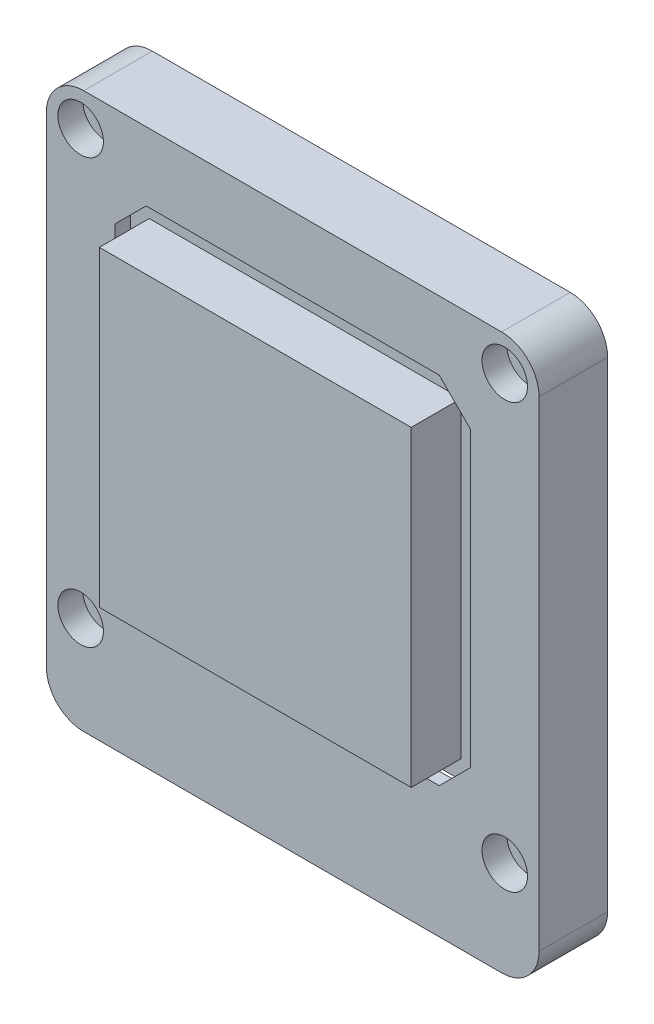
SolidWorks part; units mm, degrees
ref_plane "Front Plane" through (0, 0, 0) normal (1, 0, 0) x (0, 1, 0)
ref_plane "Top Plane" through (0, 0, 0) normal (0, 0, 1) x (0, 1, 0)
ref_plane "Right Plane" through (0, 0, 0) normal (0, 1, 0) x (-1, 0, 0)
sketch "Sketch1" plane through (0, 0, 0) normal (0, 0, 1) x (0, 1, 0)
  line L0 (0, 28) -> (28, 0) construction
  line L1 (0, 0) -> (28, 0)
  line L2 (0, 0) -> (0, 28)
  line L3 (0, 28) -> (28, 28)
  line L4 (28, 0) -> (28, 28)
  line L5 (28, 28) -> (0, 0) construction
  line L7 (1, 28) -> (1, 27) construction
extrude "Boss-Extrude1" add sketch "Sketch1" along normal blind 8.5
sketch "Sketch4" plane through (0, 0, 0) normal (0, 0, -1) x (1, 0, 0)
  line L17 (-28.5, 0.5) -> (-30.5, 0.5) construction
  line L18 (-28.5, 0.5) -> (-28.5, 2.5) construction
  line L19 (-28.5, 2.5) -> (-30.5, 2.5) construction
  line L20 (-30.5, 0.5) -> (-30.5, 2.5) construction
  line L21 (0.5, -28.5) -> (2.5, -28.5) construction
  line L22 (0.5, -28.5) -> (0.5, -30.5) construction
  line L23 (0.5, -30.5) -> (2.5, -30.5) construction
  line L24 (2.5, -28.5) -> (2.5, -30.5) construction
  line L25 (-30.5, 2.5) -> (2.5, 2.5) construction
  line L26 (-30.5, 2.5) -> (-30.5, -30.5) construction
  line L27 (-30.5, -30.5) -> (2.5, -30.5) construction
  line L28 (2.5, 2.5) -> (2.5, -30.5) construction
  line L29 (0, -28) -> (0.25, -28) construction
  line L30 (0, -28) -> (0, -28.25) construction
  line L31 (0, -28.25) -> (0.25, -28.25) construction
  line L32 (0.25, -28) -> (0.25, -28.25) construction
  line L33 (-28, 0) -> (-28.25, 0) construction
  line L34 (-28, 0) -> (-28, 0.25) construction
  line L35 (-28, 0.25) -> (-28.25, 0.25) construction
  line L36 (-28.25, 0) -> (-28.25, 0.25) construction
  line L37 (-28.25, 0.25) -> (0.25, 0.25)
  line L38 (-28.25, 0.25) -> (-28.25, -28.25)
  line L39 (-28.25, -28.25) -> (0.25, -28.25)
  line L40 (0.25, 0.25) -> (0.25, -28.25)
  line L41 (-30.5, 2.5) -> (-33.75, 2.5) construction
  line L42 (-30.5, 2.5) -> (-30.5, 5.75) construction
  line L44 (-33.75, 2.5) -> (-33.75, 5.75) construction
  line L45 (2.5, -30.5) -> (5.75, -30.5) construction
  line L46 (2.5, -30.5) -> (2.5, -33.75) construction
  line L47 (2.5, -33.75) -> (5.75, -33.75) construction
  line L48 (5.75, -30.5) -> (5.75, -33.75) construction
  line L50 (-33.75, 5.75) -> (-33.75, -33.75)
  line L51 (-33.75, -33.75) -> (5.75, -33.75)
  line L52 (5.75, 5.75) -> (5.75, -33.75)
  line L54 (-33.75, 5.75) -> (-33.75, 10.75)
  line L55 (-33.75, 10.75) -> (5.75, 10.75)
  line L56 (5.75, 5.75) -> (5.75, 10.75)
extrude "Boss-Extrude2" add sketch "Sketch4" against normal blind 5.5 separate body contours L28 L25 L26 L27 L37 L40 L39 L38
sketch "Sketch5" plane through (0, 0, 5.5) normal (0, 0, 1) x (1, 0, 0)
  line L3 (-28.5, 25.5) -> (-25.5, 25.5) construction
  line L4 (-25.5, 28.5) -> (-25.5, 25.5) construction
  line L5 (-2.5, 25.5) -> (0.5, 25.5) construction
  line L6 (-2.5, 28.5) -> (-2.5, 25.5) construction
  line L8 (-2.5, 2.5) -> (0.5, 2.5) construction
  line L10 (-2.5, 2.5) -> (-2.5, -0.5) construction
  line L14 (-28.5, 2.5) -> (-25.5, 2.5) construction
  line L15 (-25.5, 2.5) -> (-25.5, -0.5) construction
  line L16 (-28.25, 25.75) -> (-25.75, 28.25)
  line L19 (-2.25, 28.25) -> (0.25, 25.75)
  line L24 (-2.25, -0.25) -> (0.25, 2.25)
  line L27 (-25.75, -0.25) -> (-28.25, 2.25)
  line L28 (-28.25, 28.25) -> (-28.25, 25.75)
  line L29 (-28.25, -0.25) -> (-28.25, 28.25) construction
  line L30 (-28.25, 28.25) -> (-25.75, 28.25)
  line L31 (-28.25, 28.25) -> (0.25, 28.25) construction
  line L32 (0.25, 28.25) -> (-2.25, 28.25)
  line L33 (0.25, 28.25) -> (0.25, 25.75)
  line L34 (0.25, -0.25) -> (0.25, 28.25) construction
  line L35 (0.25, -0.25) -> (0.25, 2.25)
  line L36 (0.25, -0.25) -> (-2.25, -0.25)
  line L37 (-28.25, -0.25) -> (0.25, -0.25) construction
  line L38 (-28.25, -0.25) -> (-25.75, -0.25)
  line L39 (-28.25, -0.25) -> (-28.25, 2.25)
extrude "Boss-Extrude3" add sketch "Sketch5" against normal blind 0.75
sketch "Sketch6" plane through (0, 0, 0) normal (0, 0, -1) x (1, 0, 0)
  line L0 (-28, 0) -> (0, -28) construction
  line L1 (0, 0) -> (-28, -28) construction
  line L3 (-26.5, -26.5) -> (-1.5, -26.5)
  line L4 (-26.5, -26.5) -> (-26.5, -1.5)
  line L5 (-26.5, -1.5) -> (-1.5, -1.5)
  line L6 (-1.5, -26.5) -> (-1.5, -1.5)
  line L7 (-26.5, -26.5) -> (-1.5, -1.5) construction
  line L8 (-26.5, -1.5) -> (-1.5, -26.5) construction
  line L9 (-28, 0) -> (0, 0)
  line L10 (-28, 0) -> (-28, -28)
  line L11 (-28, -28) -> (0, -28)
  line L12 (0, 0) -> (0, -28)
  point P8 (-14, -14)
  line M11 (0, 0) -> (-28, 0)
  line M12 (-28, 0) -> (-28, -28)
  line M13 (-28, -28) -> (0, -28)
  line M14 (0, -28) -> (0, 0)
extrude "Cut-Extrude4" cut sketch "Sketch6" against normal blind 3 contours L6 L3 L4 L5 M14 M11 M12 M13
sketch "Sketch7" plane through (0, 0, 8.5) normal (0, 0, 1) x (1, 0, 0)
  line L0 (-28, 28) -> (0, 0) construction
  line L1 (-28, 28) -> (0, 28)
  line L2 (-28, 28) -> (-28, 0)
  line L3 (-28, 0) -> (0, 0)
  line L4 (0, 28) -> (0, 0)
  line L5 (0, 28) -> (-28, 0) construction
  line L11 (-24.9939, 3.0061) -> (-3.0061, 24.9939) construction
  line L12 (-24.9939, 24.9939) -> (-3.0061, 3.0061) construction
  line L13 (-26.5, 1.5) -> (-1.5, 1.5)
  line L14 (-26.5, 1.5) -> (-26.5, 26.5)
  line L15 (-26.5, 26.5) -> (-1.5, 26.5)
  line L16 (-1.5, 1.5) -> (-1.5, 26.5)
  line L17 (-26.5, 1.5) -> (-1.5, 26.5) construction
  line L18 (-26.5, 26.5) -> (-1.5, 1.5) construction
  point P6 (-14, 14)
  point P11 (-14, 14)
  line M15 (-28, 0) -> (0, 0)
  line M16 (0, 0) -> (0, 28)
  line M17 (0, 28) -> (-28, 28)
  line M18 (-28, 28) -> (-28, 0)
extrude "Cut-Extrude5" cut sketch "Sketch7" against normal blind 4 contours L16 L13 L14 L15 M18 M15 M16 M17
sketch "Sketch8" plane through (0, 0, 0) normal (0, 0, -1) x (1, 0, 0)
  line L0 (0.25, -28.25) -> (5.75, -33.75) construction
  line L1 (0.25, -28.25) -> (5.75, -28.25) construction
  line L2 (0.25, -28.25) -> (0.25, -33.75) construction
  line L3 (0.25, -33.75) -> (5.75, -33.75) construction
  line L4 (5.75, -28.25) -> (5.75, -33.75) construction
  line L5 (5.75, -28.25) -> (0.25, -33.75) construction
  line L6 (-33.75, 5.75) -> (-28.25, 0.25) construction
  line L7 (-33.75, 5.75) -> (-28.25, 5.75) construction
  line L8 (-33.75, 0.25) -> (-28.25, 0.25) construction
  line L9 (-33.75, 5.75) -> (-33.75, 0.25) construction
  line L10 (-28.25, 5.75) -> (-33.75, 0.25) construction
  line L11 (-28.25, 5.75) -> (-28.25, 0.25) construction
  line L12 (0.25, 5.75) -> (0.25, 0.25) construction
  line L13 (0.25, 0.25) -> (5.75, 0.25) construction
  line L14 (0.25, 5.75) -> (5.75, 0.25) construction
  line L15 (5.75, 5.75) -> (0.25, 0.25) construction
  line L16 (0.25, 5.75) -> (5.75, 5.75) construction
  line L17 (5.75, 5.75) -> (5.75, 0.25) construction
  line L18 (-33.75, -33.75) -> (-28.25, -33.75) construction
  line L19 (-33.75, -28.25) -> (-28.25, -28.25) construction
  line L20 (-33.75, -28.25) -> (-28.25, -33.75) construction
  line L21 (-33.75, -28.25) -> (-33.75, -33.75) construction
  line L22 (-28.25, -28.25) -> (-28.25, -33.75) construction
  line L23 (-28.25, -28.25) -> (-33.75, -33.75) construction
sketch "Sketch9" plane through (0, 0, 0) normal (0, 0, -1) x (1, 0, 0)
  line L0 (-33.75, 5.75) -> (-28.25, 0.25) construction
  line L1 (0.25, 5.75) -> (5.75, 0.25) construction
  line L2 (0.25, -28.25) -> (5.75, -33.75) construction
  line L3 (-33.75, -28.25) -> (-28.25, -33.75) construction
  line L4 (-31, 5.75) -> (-33.75, 5.75) construction
  line L5 (-28.25, 0.25) -> (-33.75, 0.25) construction
  line L6 (-28.25, 0.25) -> (-28.25, 5.75) construction
  line L7 (-28.25, 5.75) -> (-33.75, 5.75) construction
  line L8 (-33.75, 0.25) -> (-33.75, 5.75) construction
  line L9 (-33.75, 5.75) -> (-33.75, 3) construction
  line L10 (3, 5.75) -> (5.75, 5.75) construction
  line L11 (0.25, 0.25) -> (5.75, 0.25) construction
  line L12 (0.25, 0.25) -> (0.25, 5.75) construction
  line L13 (0.25, 5.75) -> (5.75, 5.75) construction
  line L14 (5.75, 0.25) -> (5.75, 5.75) construction
  line L15 (5.75, 5.75) -> (5.75, 3) construction
  line L16 (3, -33.75) -> (5.75, -33.75) construction
  line L17 (5.75, -33.75) -> (5.75, -31) construction
  line L18 (-31, -33.75) -> (-33.75, -33.75) construction
  line L19 (-33.75, -33.75) -> (-33.75, -31) construction
  circle A0 centre (-31, 3) radius 2.75 construction
  circle A1 centre (3, 3) radius 2.75 construction
  circle A2 centre (3, -31) radius 2.75 construction
  circle A3 centre (-31, -31) radius 2.75 construction
  arc A4 (-33.75, 3) -> (-31, 5.75) centre (-31, 3) cw construction
  arc A5 (5.75, 3) -> (3, 5.75) centre (3, 3) ccw construction
  arc A6 (5.75, -31) -> (3, -33.75) centre (3, -31) cw construction
  arc A7 (-33.75, -31) -> (-31, -33.75) centre (-31, -31) ccw construction
  circle A8 centre (-31, 3) radius 0.95
  circle A9 centre (3, 3) radius 0.95
  circle A10 centre (3, -31) radius 0.95
  circle A11 centre (-31, -31) radius 0.95
extrude "Cut-Extrude7" cut sketch "Sketch9" against normal blind 5.5
sketch "Sketch13" plane through (0, 0, 5.5) normal (0, 0, 1) x (1, 0, 0)
  line L0 (-33.75, 28.25) -> (-28.25, 33.75) construction
  line L1 (0.25, 28.25) -> (5.75, 33.75) construction
  line L2 (0.25, -5.75) -> (5.75, -0.25) construction
  line L3 (-33.75, -5.75) -> (-28.25, -0.25) construction
  circle A0 centre (-31, 31) radius 1.825
  circle A1 centre (3, 31) radius 1.825
  circle A2 centre (3, -3) radius 1.825
  circle A3 centre (-31, -3) radius 1.825
extrude "Cut-Extrude8" cut sketch "Sketch13" against normal blind 2
sketch "Sketch14" plane through (0, 0, 0) normal (0, 0, -1) x (1, 0, 0)
  line L0 (0.25, 5.75) -> (0.25, 8.9603) construction
  line L2 (-28.25, 0.25) -> (0.25, 0.25)
  line L3 (-28.25, 0.25) -> (-28.25, 8.9603)
  line L4 (-28.25, 8.9603) -> (0.25, 8.9603)
  line L5 (0.25, 0.25) -> (0.25, 8.9603)
extrude "Cut-Extrude9" cut sketch "Sketch14" against normal blind 4.5 contours L3 L2 L5 L4
fillet "Fillet2" radius 3 4 edges at (-33.75, 33.75, 2.75) (5.75, 33.75, 2.75) (5.75, -10.75, 2.75) (-33.75, -10.75, 2.75)
sketch "Sketch15" plane through (0, 0, 4.75) normal (0, 0, -1) x (1, 0, 0)
  line L3 (0.25, 0.25) -> (-2.25, 0.25)
  line L4 (-2.25, 0.25) -> (0.25, -2.25)
  line L5 (0.25, -2.25) -> (0.25, 0.25)
  line L6 (0.25, 0.25) -> (-2.25, 0.25)
  line L7 (-2.25, 0.25) -> (0.25, -2.25)
  line L8 (0.25, -2.25) -> (0.25, 0.25)
  line L9 (-28.25, 0.25) -> (-28.25, -2.25)
  line L10 (-28.25, -2.25) -> (-25.75, 0.25)
  line L11 (-25.75, 0.25) -> (-28.25, 0.25)
  line L12 (-28.25, 0.25) -> (-28.25, -2.25)
  line L13 (-28.25, -2.25) -> (-25.75, 0.25)
  line L14 (-25.75, 0.25) -> (-28.25, 0.25)
  line L15 (-28.25, -28.25) -> (-25.75, -28.25)
  line L16 (-25.75, -28.25) -> (-28.25, -25.75)
  line L17 (-28.25, -25.75) -> (-28.25, -28.25)
  line L18 (-28.25, -28.25) -> (-25.75, -28.25)
  line L19 (-25.75, -28.25) -> (-28.25, -25.75)
  line L20 (-28.25, -25.75) -> (-28.25, -28.25)
  line L21 (0.25, -28.25) -> (0.25, -25.75)
  line L22 (0.25, -25.75) -> (-2.25, -28.25)
  line L23 (-2.25, -28.25) -> (0.25, -28.25)
  line L24 (0.25, -28.25) -> (0.25, -25.75)
  line L25 (0.25, -25.75) -> (-2.25, -28.25)
  line L26 (-2.25, -28.25) -> (0.25, -28.25)
  dimension "D1" = 0
  dimension "D2" = 0
  dimension "D3" = 0
  dimension "D4" = 0
extrude "Boss-Extrude4" add sketch "Sketch15" along normal blind 0.25
